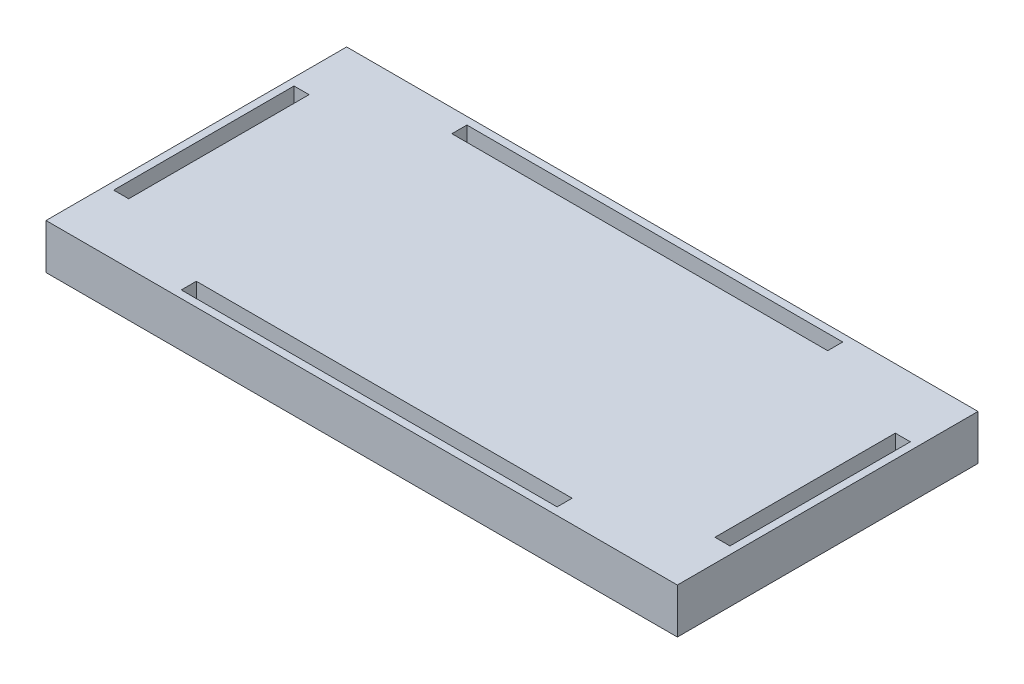
SolidWorks part; units mm, degrees
ref_plane "Front Plane" through (0, 0, 0) normal (0, 0, 1) x (1, 0, 0)
ref_plane "Top Plane" through (0, 0, 0) normal (0, 1, 0) x (1, 0, 0)
ref_plane "Right Plane" through (0, 0, 0) normal (1, 0, 0) x (0, 0, -1)
sketch "Sketch1" plane through (0, 0, 0) normal (0, 1, 0) x (1, 0, 0)
  line L0 (-105, 48) -> (-105, 50)
  line L1 (103, -50) -> (-103, -50)
  line L2 (105, -48) -> (105, 48)
  line L3 (103, 50) -> (-103, 50)
  line L4 (-105, -48) -> (-105, 48)
  line L5 (105, -50) -> (-105, 50) construction
  line L6 (105, 50) -> (-105, -50) construction
  line L7 (-105, 50) -> (-103, 50)
  line L8 (105, 48) -> (105, 50)
  line L9 (105, 50) -> (103, 50)
  line L10 (-105, -48) -> (-105, -50)
  line L11 (-105, -50) -> (-103, -50)
  line L12 (103, -50) -> (105, -50)
  line L13 (105, -50) -> (105, -48)
  point P0 (0, 0)
extrude "Boss-Extrude1" add sketch "Sketch1" along normal blind 15 contours L4 L0 L7 L3 L9 L8 L2 L13 L12 L1 L11 L10
sketch "Sketch2" plane through (0, 15, 0) normal (0, 1, 0) x (1, 0, 0)
  line L8 (-95, -40) -> (95, -40)
  line L9 (95, -40) -> (95, 40)
  line L10 (95, 40) -> (-95, 40)
  line L11 (-95, 40) -> (-95, -40)
  line L12 (-95, -40) -> (95, -40)
  line L13 (95, -40) -> (95, 40)
  line L14 (95, 40) -> (-95, 40)
  line L15 (-95, 40) -> (-95, -40)
  dimension "D1" = 10
sketch "Sketch5" plane through (0, 15, 0) normal (0, 1, 0) x (1, 0, 0)
  line L0 (0, 0) -> (-15.1345, 0) construction
  line L1 (105, 50) -> (-105, 50) construction
  line L3 (97.5, 30) -> (102.5, 30)
  line L5 (-105, -50) -> (-105, 50) construction
  line L7 (-95, 40) -> (-95, -40) construction
  line L8 (-95, 0) -> (-105, 0) construction
  line L9 (-97.5, -30) -> (-102.5, -30)
  line L10 (-97.5, -30) -> (-97.5, 30)
  line L11 (-97.5, 30) -> (-102.5, 30)
  line L12 (-102.5, -30) -> (-102.5, 30)
  line L13 (-97.5, -30) -> (-102.5, 30) construction
  line L14 (-97.5, 30) -> (-102.5, -30) construction
  line L15 (102.5, -30) -> (102.5, 30)
  line L16 (97.5, -30) -> (102.5, -30)
  line L17 (97.5, -30) -> (97.5, 30)
  line L18 (0, 40) -> (0, 50) construction
  line L19 (95, 40) -> (-95, 40) construction
  line L20 (62.5, -47.5) -> (-62.5, -47.5)
  line L21 (62.5, 42.5) -> (-62.5, 42.5)
  line L22 (62.5, 42.5) -> (62.5, 47.5)
  line L23 (62.5, 47.5) -> (-62.5, 47.5)
  line L24 (-62.5, 42.5) -> (-62.5, 47.5)
  line L25 (62.5, 42.5) -> (-62.5, 47.5) construction
  line L26 (62.5, 47.5) -> (-62.5, 42.5) construction
  line L27 (-62.5, -42.5) -> (-62.5, -47.5)
  line L28 (62.5, -42.5) -> (-62.5, -42.5)
  line L29 (62.5, -42.5) -> (62.5, -47.5)
  point P5 (0, 45)
  point P6 (-100, 0)
extrude "Cut-Extrude2" cut sketch "Sketch5" against normal blind 5
